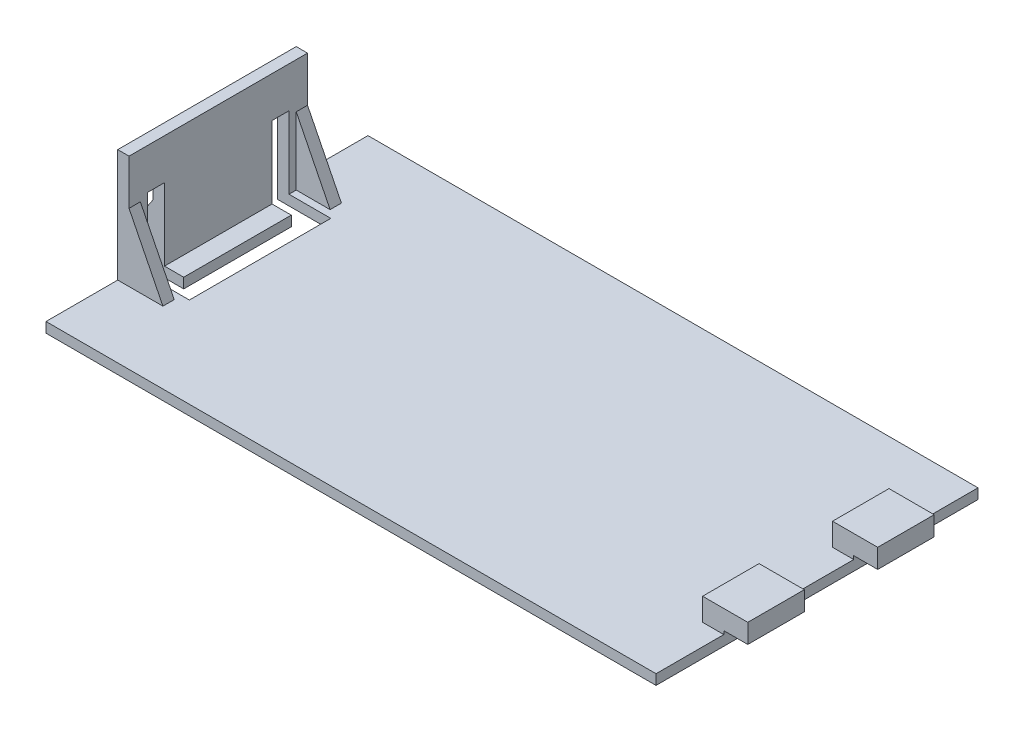
SolidWorks part; units mm, degrees
ref_plane "Alzado" through (0, 0, 0) normal (0, 0, 1) x (1, 0, 0)
ref_plane "Planta" through (0, 0, 0) normal (0, 1, 0) x (1, 0, 0)
ref_plane "Vista lateral" through (0, 0, 0) normal (1, 0, 0) x (0, 0, -1)
sketch "Croquis1" plane through (0, 0, 0) normal (0, 1, 0) x (1, 0, 0)
  line L0 (-13.7413, -0.507) -> (-13.7413, -12.507)
  line L1 (-13.7413, 15.993) -> (40.2587, 15.993)
  line L2 (-13.7413, 15.993) -> (-13.7413, 3.993)
  line L3 (-13.7413, -12.507) -> (40.2587, -12.507)
  line L4 (40.2587, 15.993) -> (40.2587, -12.507)
  line L5 (-13.7413, 3.993) -> (-15.1913, 3.993)
  line L7 (-13.7413, -0.507) -> (-15.1913, -0.507)
  line L8 (-15.1913, 3.993) -> (-15.1913, -0.507)
  dimension "D1" = 54
  dimension "D2" = 28.5
extrude "Saliente-Extruir1" add sketch "Croquis1" along normal blind 0.9
sketch "Croquis2" plane through (0, 0.9, 0) normal (0, 1, 0) x (1, 0, 0)
  line L0 (-13.7413, -12.507) -> (40.2587, -12.507) construction
  line L1 (38.3803, -1.507) -> (40.2587, -1.507)
  line L2 (38.3803, -1.507) -> (38.3803, -6.507)
  line L3 (38.3803, -6.507) -> (40.2587, -6.507)
  line L4 (40.2587, -1.507) -> (40.2587, -6.507)
  line L5 (40.2587, 15.993) -> (-13.7413, 15.993) construction
  line L6 (38.3803, 4.993) -> (40.2587, 4.993)
  line L7 (38.3803, 4.993) -> (38.3803, 9.993)
  line L8 (38.3803, 9.993) -> (40.2587, 9.993)
  line L9 (40.2587, 4.993) -> (40.2587, 9.993)
  dimension "D1" = 6
  dimension "D2" = 6
extrude "Saliente-Extruir2" add sketch "Croquis2" along normal blind 0.3
sketch "Croquis3" plane through (0, 1.2, 0) normal (0, 1, 0) x (1, 0, 0)
  line L1 (38.3803, -6.507) -> (42.3803, -6.507)
  line L2 (38.3803, -6.507) -> (38.3803, -1.507)
  line L3 (38.3803, -1.507) -> (42.3803, -1.507)
  line L4 (42.3803, -6.507) -> (42.3803, -1.507)
extrude "Saliente-Extruir4" add sketch "Croquis3" along normal blind 1.7
sketch "Croquis4" plane through (0, 1.2, 0) normal (0, 1, 0) x (1, 0, 0)
  line L1 (38.3803, 4.993) -> (42.3803, 4.993)
  line L2 (38.3803, 4.993) -> (38.3803, 9.993)
  line L3 (38.3803, 9.993) -> (42.3803, 9.993)
  line L4 (42.3803, 4.993) -> (42.3803, 9.993)
extrude "Saliente-Extruir5" add sketch "Croquis4" along normal blind 1.7
sketch "Croquis5" plane through (0, 0.9, 0) normal (0, 1, 0) x (1, 0, 0)
  line L2 (-13.7413, -0.507) -> (-13.7413, -12.507) construction
  line L3 (-13.7413, -6.157) -> (-12.7413, -6.157)
  line L4 (-13.7413, -6.157) -> (-13.7413, 9.643)
  line L5 (-13.7413, 9.643) -> (-12.7413, 9.643)
  line L6 (-12.7413, -6.157) -> (-12.7413, 9.643)
extrude "Saliente-Extruir6" add sketch "Croquis5" along normal blind 10
sketch "Croquis6" plane through (0, 0, -9.643) normal (0, 0, -1) x (-1, 0, 0)
  line L0 (13.7413, 2.5) -> (13.7413, 5.5)
  line L4 (13.7413, 10.9) -> (13.7413, 0.9) construction
  line L5 (13.7413, 2.5) -> (15.7413, 2.5)
  line L6 (15.7413, 2.5) -> (13.7413, 5.5)
sketch "Croquis7" plane through (-13.7413, 0, 0) normal (-1, 0, 0) x (0, 0, 1)
  line L0 (-9.643, 7.41) -> (-6.503, 7.41)
  line L1 (-9.643, 10.9) -> (-9.643, 0.9) construction
  dimension "D1" = 3.14
extrude "Saliente-Extruir8" add sketch "Croquis6" against normal blind 2.16 from vertex at -3.14 contours L6 L0 L5 starting at point (-13.7413, 7.41, -6.503)
sketch "Croquis9" plane through (0, 0, 6.157) normal (0, 0, 1) x (1, 0, 0)
  line L0 (-15.7413, 2.5) -> (-13.7413, 5.5)
  line L1 (-13.7413, 5.5) -> (-13.7413, 2.5)
  line L2 (-13.7413, 2.5) -> (-13.7413, 5.5) construction
  line L3 (-13.7413, 2.5) -> (-15.7413, 2.5) construction
  line L4 (-13.7413, 2.5) -> (-15.7413, 2.5)
sketch "Croquis10" plane through (-13.7413, 0, 0) normal (-1, 0, 0) x (0, 0, 1)
  line L0 (6.157, 2.5) -> (3.017, 2.5)
  dimension "D1" = 3.14
extrude "Saliente-Extruir9" add sketch "Croquis9" against normal blind 2.16 from vertex at -3.14 contours L4 L0 L1 starting at point (-13.7413, 2.5, 3.017)
sketch "Croquis12" plane through (0, 0, -9.643) normal (0, 0, -1) x (-1, 0, 0)
  line L0 (12.7413, 0.9) -> (9.7413, 0.9)
  line L1 (-40.2587, 0.9) -> (13.7413, 0.9) construction
  line L2 (9.7413, 0.9) -> (12.7413, 6.9)
  line L3 (12.7413, 10.9) -> (12.7413, 0.9) construction
  line L4 (12.7413, 6.9) -> (12.7413, 0.9)
extrude "Saliente-Extruir10" add sketch "Croquis12" against normal blind 1
sketch "Croquis13" plane through (0, 0, 6.157) normal (0, 0, 1) x (1, 0, 0)
  line L0 (-12.7413, 0.9) -> (-9.7413, 0.9)
  line L1 (-9.7413, 0.9) -> (-12.7413, 6.9)
  line L2 (-12.7413, 6.9) -> (-12.7413, 0.9)
extrude "Saliente-Extruir11" add sketch "Croquis13" against normal blind 1
sketch "Croquis14" plane through (-13.7413, 0, 0) normal (-1, 0, 0) x (0, 0, 1)
  line L0 (0.507, 0) -> (12.507, 0) construction
  line L2 (-15.993, 0) -> (-3.993, 0) construction
  line L3 (3.017, 7.3) -> (4.517, 7.3)
  line L4 (3.017, 7.3) -> (3.017, 0)
  line L5 (3.017, 0) -> (4.517, 0)
  line L6 (4.517, 7.3) -> (4.517, 0)
  line L7 (-6.503, 0) -> (-8.003, 0)
  line L8 (-6.503, 0) -> (-6.503, 7.3)
  line L9 (-6.503, 7.3) -> (-8.003, 7.3)
  line L10 (-8.003, 0) -> (-8.003, 7.3)
extrude "Cortar-Extruir1" cut sketch "Croquis14" against normal blind 4.7
sketch "Croquis16" plane through (0, 0.9, 0) normal (0, 1, 0) x (1, 0, 0)
  line L0 (-12.7413, -3.017) -> (-9.0413, -3.017) construction
  line L1 (-9.0413, 6.503) -> (-11.0413, 6.503)
  line L2 (-9.0413, 6.503) -> (-9.0413, -3.017)
  line L3 (-9.0413, -3.017) -> (-11.0413, -3.017)
  line L4 (-11.0413, 6.503) -> (-11.0413, -3.017)
extrude "Cortar-Extruir2" cut sketch "Croquis16" against normal blind 4.7
